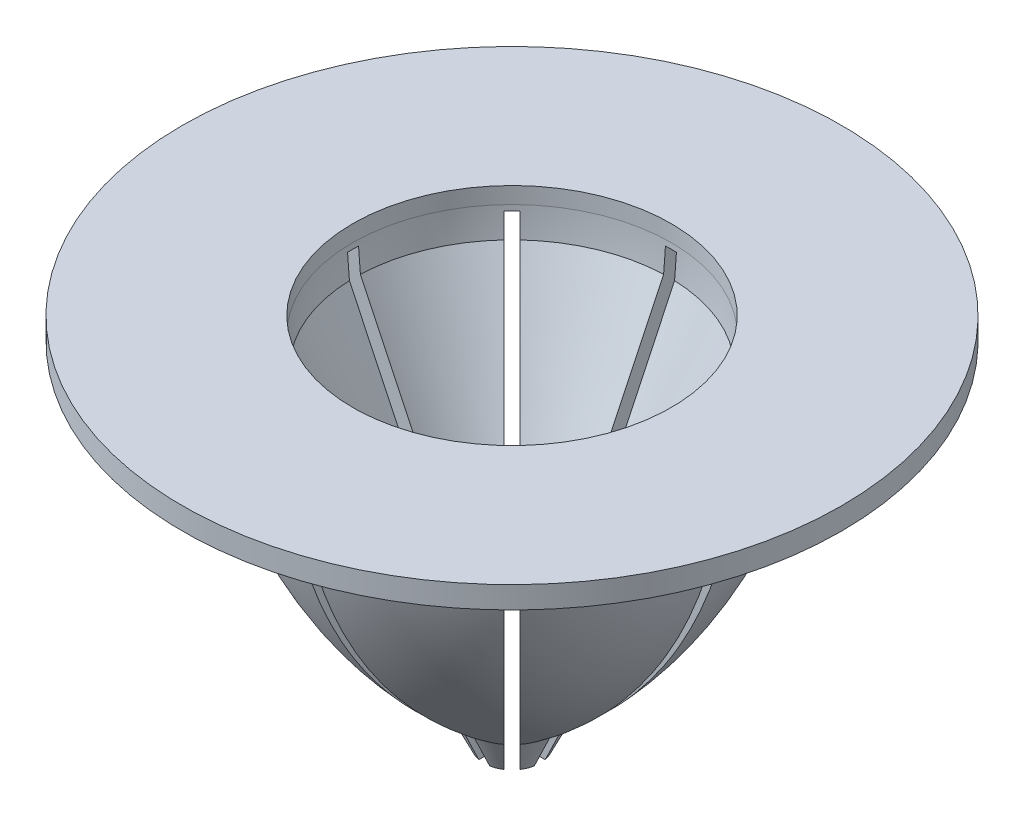
SolidWorks part; units mm, degrees
ref_plane "前视基准面" through (0, 0, 0) normal (0, 0, 1) x (1, 0, 0)
ref_plane "上视基准面" through (0, 0, 0) normal (0, 1, 0) x (1, 0, 0)
ref_plane "右视基准面" through (0, 0, 0) normal (1, 0, 0) x (0, 0, -1)
sketch "草图1" plane through (0, 0, 0) normal (0, 0, 1) x (1, 0, 0)
  line L2 (20, 0) -> (30, 0)
  line L3 (30, 0) -> (30, 2)
  line L4 (30, 2) -> (14.5, 2)
  line L7 (0, 0) -> (0, -25)
  line L8 (4, -29) -> (0.187, -37.0228)
  line L10 (14.5, 0.5) -> (14.5, 2)
  line L12 (0.187, -31.8641) -> (9.517, -12.233)
  line L14 (0.187, -31.8641) -> (0.187, -37.0228)
  line L15 (9.517, -12.233) -> (14.3092, -2.1498)
  arc A0 (14.5, 0.5) -> (14.3092, -2.1498) centre (-25.4701, 2.0465) cw
  arc A1 (4, -29) -> (20, 0) centre (-19.8805, 3.0893) ccw
  dimension "D1" = 20
  dimension "D3" = 2
  dimension "D4" = 10
  dimension "D5" = 15.5
  dimension "D6" = 25
revolve "旋转1" add sketch "草图1" angle 360 about L7
sketch "草图4" plane through (0, 0, 0) normal (1, 0, 0) x (0, 0, -1)
  line L2 (-0.5, -29) -> (-0.5, 0)
  line L3 (-20, 0) -> (20, 0) construction
  line L4 (-0.5, 0) -> (0.5, 0)
  line L5 (0.5, 0) -> (0.5, -29)
  line L7 (-0.5, -29) -> (-0.5, -40.2202)
  line L8 (-0.5, -40.2202) -> (0.5, -40.2202)
  line L9 (0.5, -40.2202) -> (0.5, -29)
  dimension "D1" = 0.5
  dimension "D2" = 1
  dimension "Slot_Shoulder_Depth" = 29
  dimension "Slot_Cut_Extent" = 40.2202
extrude "切除-拉伸2" cut sketch "草图4" against normal through all both and the other way through all contours L9 L8 L7 L2 L4 L5
sketch "草图5" plane through (0, 0, 0) normal (0, 0, 1) x (1, 0, 0)
  line L0 (0, 3.646) -> (0, -5.8617) construction
  line L1 (0, 3.646) -> (0, -14.0888)
ref_plane "基准面1" through (0, 0, 0) normal (-0.7071, 0, 0.7071) x (0, -1, 0)
ref_plane "基准面2" through (0, 0, 0) normal (-0.7071, 0, -0.7071) x (0, -1, 0)
sketch "草图6" plane through (0, 0, 0) normal (-0.7071, 0, -0.7071) x (0, -1, 0)
  line L9 (0, -0.5) -> (0, 0.5)
  line L10 (0, -0.5) -> (45.8675, -0.5)
  line L11 (45.8675, -0.5) -> (45.8675, 0.5)
  line L12 (45.8675, 0.5) -> (0, 0.5)
  point P6 (0, 0)
  dimension "D1" = 0.5
  dimension "D2" = 1
sketch "草图10" plane through (0, 0, 0) normal (0, 0, 1) x (1, 0, 0)
  line L0 (0, 0) -> (0.5, 0)
  line L1 (-19.9937, 0) -> (19.9937, 0) construction
  line L2 (0.5, 0) -> (0.5, -46.33)
  line L3 (0.5, -46.33) -> (-0.5, -46.33)
  line L4 (-0.5, -46.33) -> (-0.5, 0)
  line L5 (-0.5, 0) -> (0.5, 0)
  dimension "D1" = 0.5
  dimension "D2" = 0.5
extrude "切除-拉伸3" cut sketch "草图10" along normal through all both and the other way through all contours L2 L3 L4 L5
sketch "草图11" plane through (0, 0, 0) normal (0, 0, 1) x (1, 0, 0)
  line L0 (-0.5, -29) -> (-0.5, -32)
  line L1 (-0.5, -35.9285) -> (-0.5, -29) construction
  line L2 (-0.5, -32) -> (-4.4929, -32)
  line L3 (-4.4929, -32) -> (-4.4929, -37.7956)
  line L4 (-4.4929, -37.7956) -> (7.0711, -37.7956)
  line L5 (7.0711, -37.7956) -> (7.0711, -32)
  line L6 (7.0711, -32) -> (-0.5, -32)
  dimension "D1" = 3
extrude "切除-拉伸4" cut sketch "草图11" against normal through all both and the other way through all contours L2 L3 L4 L5 L6
sketch "草图12" plane through (0, 0, 0) normal (-0.7071, 0, -0.7071) x (0, -1, 0)
  line L1 (0, 0) -> (0, -0.5)
  line L2 (0, -13.7842) -> (0, 13.7842) construction
  line L3 (0, -0.5) -> (66.5452, -0.5)
  line L4 (66.5452, -0.5) -> (66.5452, 0.5)
  line L5 (66.5452, 0.5) -> (0, 0.5)
  line L6 (0, 0.5) -> (0, -0.5)
  dimension "D1" = 0.5
  dimension "D2" = 0.5
extrude "切除-拉伸5" cut sketch "草图12" against normal through all both and the other way through all contours L3 L4 L5 L6
sketch "草图13" plane through (0, 0, 0) normal (-0.7071, 0, 0.7071) x (0, -1, 0)
  line L0 (0, 0) -> (0, -0.5)
  line L1 (0, -0.5) -> (45.3526, -0.5)
  line L2 (45.3526, -0.5) -> (45.3526, 0.5)
  line L3 (45.3526, 0.5) -> (0, 0.5)
  line L4 (0, -13.7842) -> (0, 13.7842) construction
  line L5 (0, 0.5) -> (0, -0.5)
  dimension "D1" = 0.5
  dimension "D2" = 0.5
extrude "切除-拉伸6" cut sketch "草图13" against normal through all both and the other way through all contours L1 L2 L3 L5
